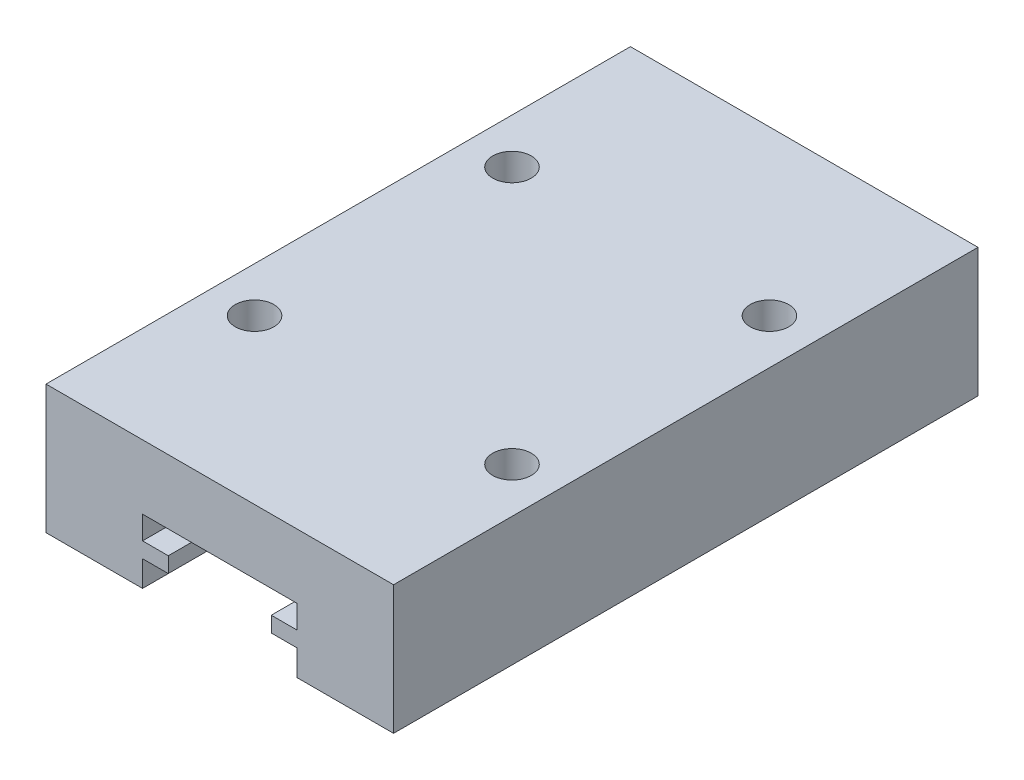
SolidWorks part; units mm, degrees
ref_plane "Plan de face" through (0, 0, 0) normal (0, 0, 1) x (1, 0, 0)
ref_plane "Plan de dessus" through (0, 0, 0) normal (0, 1, 0) x (1, 0, 0)
ref_plane "Plan de droite" through (0, 0, 0) normal (1, 0, 0) x (0, 0, -1)
sketch "Esquisse1" plane through (0, 0, 0) normal (0, 0, 1) x (1, 0, 0)
  line L0 (-22.7955, 10) -> (4.2045, 10)
  line L1 (4.2045, 10) -> (4.2045, 0)
  line L2 (4.2045, 0) -> (-3.2955, 0)
  line L3 (-3.2955, 0) -> (-3.2955, 2)
  line L4 (-3.2955, 2) -> (-5.2955, 2)
  line L5 (-5.2955, 2) -> (-5.2955, 3.2)
  line L6 (-5.2955, 3.2) -> (-3.2955, 3.2)
  line L7 (-3.2955, 3.2) -> (-3.2955, 5)
  line L8 (-3.2955, 5) -> (-15.2955, 5)
  line L9 (-15.2955, 5) -> (-15.2955, 3.2)
  line L10 (-15.2955, 3.2) -> (-13.2955, 3.2)
  line L11 (-13.2955, 3.2) -> (-13.2955, 2)
  line L12 (-13.2955, 2) -> (-15.2955, 2)
  line L13 (-15.2955, 2) -> (-15.2955, 0)
  line L14 (-15.2955, 0) -> (-22.7955, 0)
  line L15 (-22.7955, 0) -> (-22.7955, 10)
  dimension "D1" = 1.2
  dimension "D2" = 2
  dimension "D3" = 1.8
  dimension "D4" = 2
  dimension "D5" = 10
  dimension "D6" = 7.5
  dimension "D7" = 27
extrude "Boss.-Extru.1" add sketch "Esquisse1" along normal blind 45.4
sketch "Esquisse2" plane through (0, 10, 0) normal (0, 1, 0) x (1, 0, 0)
  line L0 (-19.2955, -32.7) -> (0.7045, -32.7) construction
  line L1 (0.7045, -32.7) -> (0.7045, -12.7) construction
  line L2 (4.2045, -45.4) -> (-22.7955, -45.4) construction
  line L3 (4.2045, -45.4) -> (4.2045, 0) construction
  circle A0 centre (-19.2955, -32.7) radius 1.5
  circle A1 centre (-19.2955, -12.7) radius 1.5
  circle A2 centre (0.7045, -12.7) radius 1.5
  circle A3 centre (0.7045, -32.7) radius 1.5
  point P8 (-9.2955, -32.7)
  point P11 (-9.2955, -45.4)
  point P12 (0.7045, -22.7)
  point P15 (4.2045, -22.7)
  dimension "D3" = 3
  dimension "D1" = 20
  dimension "D2" = 20
extrude "Enlèv. mat.-Extru.1" cut sketch "Esquisse2" against normal blind 3.5
